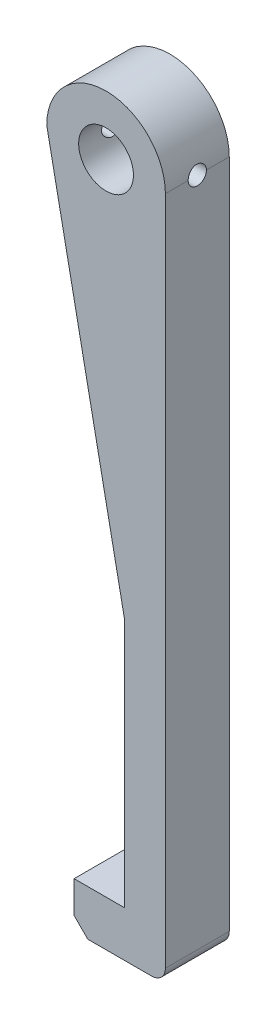
SolidWorks part; units mm, degrees
ref_plane "Front Plane" through (0, 0, 0) normal (0, 0, 1) x (1, 0, 0)
ref_plane "Top Plane" through (0, 0, 0) normal (0, 1, 0) x (1, 0, 0)
ref_plane "Right Plane" through (0, 0, 0) normal (1, 0, 0) x (0, 0, -1)
sketch "Sketch1" plane through (0, 0, 0) normal (0, 0, 1) x (1, 0, 0)
  line L0 (-202.9169, 0) -> (220.9169, 0) construction
  line L1 (0, 119.6461) -> (0, -116.4365) construction
  line L2 (0, -65) -> (-11, -65)
  line L3 (-11, -65) -> (-11, -72)
  line L4 (-11, -72) -> (-8, -75)
  line L5 (-8, -75) -> (9, -75)
  line L6 (9, -75) -> (9, 75)
  line L7 (0, -65) -> (0, -10)
  line L8 (0, -10) -> (-17, 75)
  line L9 (-71.2303, 75) -> (51.9717, 75) construction
  arc A0 (-17, 75) -> (9, 75) centre (-4, 75) cw
  circle A1 centre (-4, 75) radius 6
  point P17 (9, 0)
  dimension "D7" = 12
  dimension "D8" = 13
  dimension "D1" = 10
  dimension "D2" = 9
  dimension "D3" = 3
  dimension "D4" = 3
  dimension "D5" = 17
  dimension "65" = 65
  dimension "D6" = 140
  dimension "140" = 140
extrude "Boss-Extrude1" add sketch "Sketch1" along normal blind 14
sketch "Sketch2" plane through (9, 0, 0) normal (1, 0, 0) x (0, 0, -1)
  line L0 (-14, 75) -> (0, 75) construction
  circle A0 centre (-7, 75) radius 2
  dimension "D1" = 4
extrude "Cut-Extrude1" cut sketch "Sketch2" against normal through all
fillet "Fillet1" radius 3 1 edges at (9, -75, 7)
